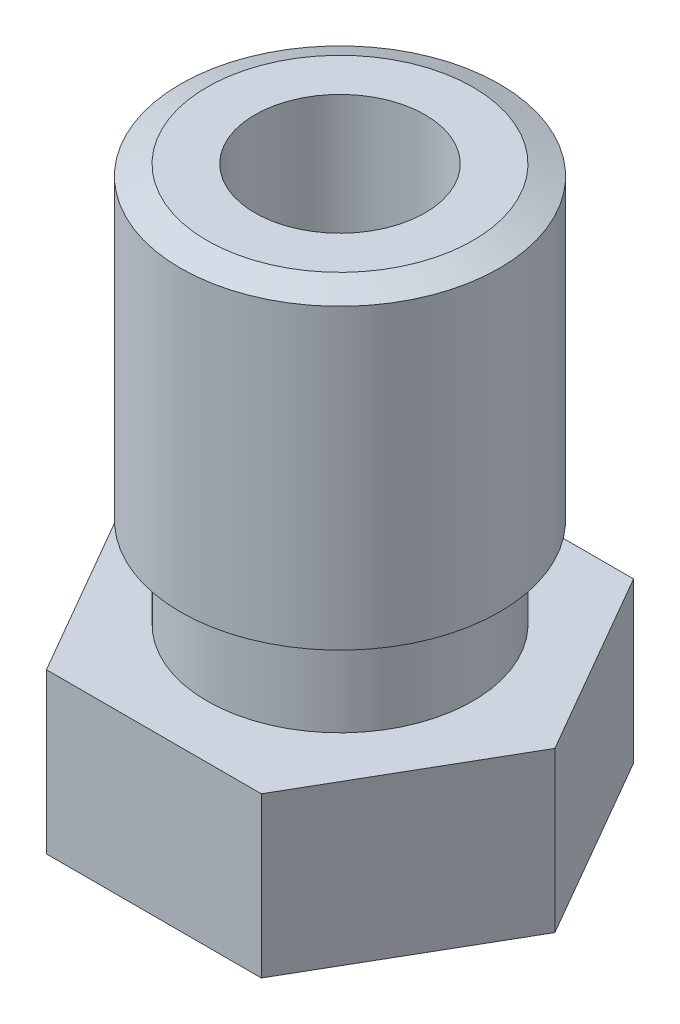
SolidWorks part; units mm, degrees
material "Brass"
ref_plane "Front Plane" through (0, 0, 0) normal (0, 0, 1) x (1, 0, 0)
ref_plane "Top Plane" through (0, 0, 0) normal (0, 1, 0) x (1, 0, 0)
ref_plane "Right Plane" through (0, 0, 0) normal (1, 0, 0) x (0, 0, -1)
sketch "Sketch1" plane through (0, 0, 0) normal (0, 0, 1) x (1, 0, 0)
  line L0 (0, 0) -> (0.5, 0)
  line L1 (0.5, 0) -> (1.9004, 2)
  line L2 (1.9004, 2) -> (3.5, 2)
  line L3 (3.5, 2) -> (3.5, 5)
  line L4 (3.5, 5) -> (2.5, 5)
  line L5 (2.5, 5) -> (2.5, 6.5)
  line L6 (2.5, 6.5) -> (3, 6.7)
  line L7 (3, 6.7) -> (3, 12.3)
  line L8 (3, 12.3) -> (2.5, 12.5)
  line L9 (2.5, 12.5) -> (0, 12.5)
  line L10 (0, 12.5) -> (0, 0)
  line L11 (0, 0) -> (0, 44.5411) construction
  dimension "D1" = 1
  dimension "D2" = 125
  dimension "D3" = 5
  dimension "D4" = 7
  dimension "D5" = 10.5
  dimension "D6" = 0.2
  dimension "D7" = 0.2
  dimension "D8" = 6
  dimension "D9" = 6
  dimension "D10" = 7.5
  dimension "D11" = 12.5
revolve "Revolve1" add sketch "Sketch1" angle 360 about L11
sketch "Sketch2" plane through (0, 5, 0) normal (0, 1, 0) x (1, 0, 0)
  line L1 (2.0207, 3.5) -> (-2.0207, 3.5)
  line L2 (-2.0207, 3.5) -> (-4.0415, 0)
  line L3 (-4.0415, 0) -> (-2.0207, -3.5)
  line L4 (-2.0207, -3.5) -> (2.0207, -3.5)
  line L5 (2.0207, -3.5) -> (4.0415, 0)
  line L6 (4.0415, 0) -> (2.0207, 3.5)
  circle A0 centre (0, 0) radius 3.5 construction
  circle A1 centre (0, 0) radius 3.5 construction
extrude "Boss-Extrude1" add sketch "Sketch2" against normal up to surface (3 mm away) up to face at (0, 2, -3.5)
sketch "Sketch3" plane through (0, 0, 0) normal (0, 0, 1) x (1, 0, 0)
  line L0 (0, 0) -> (0, 50000) construction
  line L1 (2.5, 12.5) -> (-2.5, 12.5) construction
  line L2 (0, 0) -> (0.2, 0)
  line L3 (0.2, 0) -> (0.2, 0.8)
  line L4 (0.2, 0.8) -> (0.75, 1.1175)
  line L5 (0.75, 1.1175) -> (0.75, 1.9093)
  line L6 (0.75, 1.9093) -> (1.6, 2.4)
  line L7 (1.6, 2.4) -> (1.6, 12.5)
  line L8 (1.6, 12.5) -> (0, 12.5)
  line L9 (0, 12.5) -> (0, 0)
  point P5 (0, 12.5)
  dimension "D1" = 0.4
  dimension "D2" = 1.5
  dimension "D3" = 3.2
  dimension "D4" = 0.8
  dimension "D5" = 120
  dimension "D6" = 10.1
revolve "Cut-Revolve1" cut sketch "Sketch3" angle 360 about L0
equation "\"D7@Sketch1\"=\"D6@Sketch1\""
